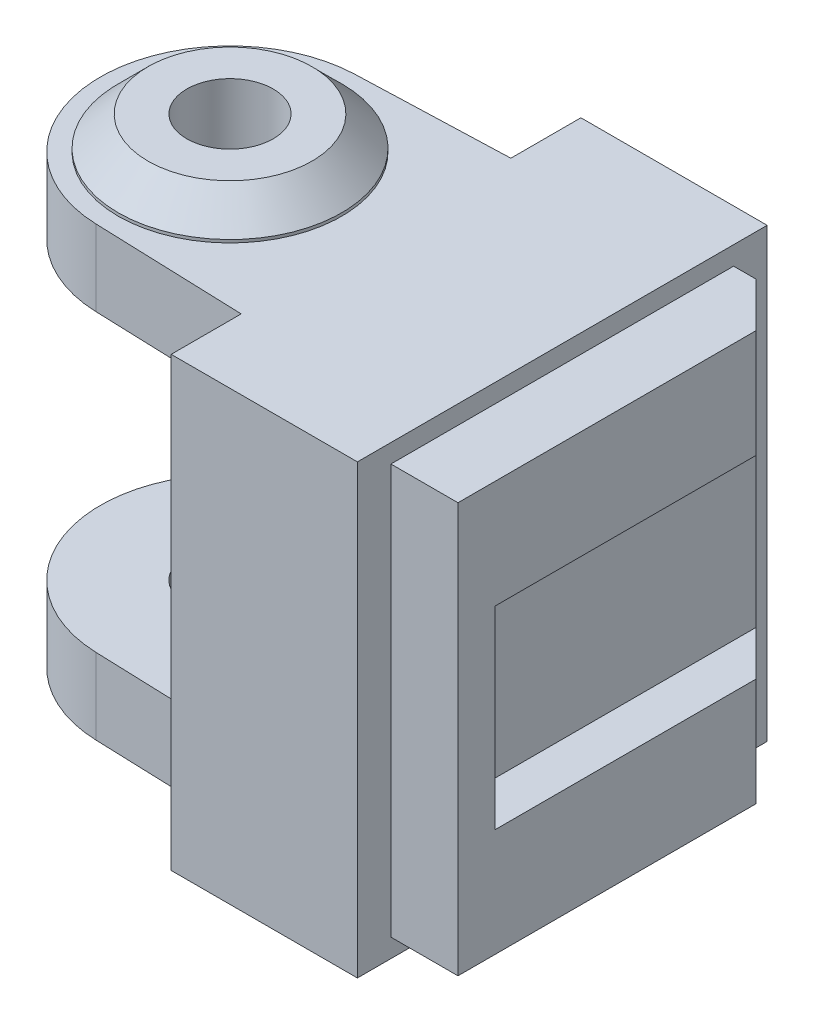
SolidWorks part; units mm, degrees
ref_plane "前视基准面" through (0, 0, 0) normal (0, 0, 1) x (1, 0, 0)
ref_plane "上视基准面" through (0, 0, 0) normal (0, 1, 0) x (1, 0, 0)
ref_plane "右视基准面" through (0, 0, 0) normal (1, 0, 0) x (0, 0, -1)
other "Configuration Table"
sketch "草图1" plane through (0, 0, 0) normal (0, 1, 0) x (1, 0, 0)
  line L0 (-0.3058, 8.6946) -> (9.8, 9.05)
  line L1 (9.8, 9.05) -> (9.8, -9.05)
  line L2 (9.8, -9.05) -> (-0.3058, -8.6946)
  line L3 (0, 0) -> (9.8, 0) construction
  circle A0 centre (0, 0) radius 2.9
  arc A1 (-0.3058, 8.6946) -> (-0.3058, -8.6946) centre (0, 0) ccw
  dimension "D1" = 5.8
  dimension "D4" = 17.4
  dimension "D2" = 9.8
  dimension "D3" = 18.1
extrude "凸台-拉伸1" add sketch "草图1" along normal blind 30
sketch "草图2" plane through (9.8, 0, 0) normal (1, 0, 0) x (0, 0, -1)
  line L0 (0, 30) -> (0, 0) construction
  line L1 (-13.75, 30) -> (13.75, 30)
  line L2 (-13.75, 30) -> (-13.75, 0)
  line L3 (-13.75, 0) -> (13.75, 0)
  line L4 (13.75, 30) -> (13.75, 0)
  line L5 (-9.05, 30) -> (9.05, 30) construction
  line L6 (-9.05, 0) -> (9.05, 0) construction
  dimension "D1" = 27.5
extrude "凸台-拉伸2" add sketch "草图2" along normal blind 17
sketch "草图3" plane through (9.8, 0, 0) normal (-1, 0, 0) x (0, 0, 1)
  line L0 (-13.75, 0) -> (-13.75, 30) construction
  line L1 (-13.75, 24.9) -> (13.75, 24.9)
  line L2 (-13.75, 24.9) -> (-13.75, 5.1)
  line L3 (-13.75, 5.1) -> (13.75, 5.1)
  line L4 (13.75, 24.9) -> (13.75, 5.1)
  line L5 (13.75, 30) -> (13.75, 0) construction
  line L6 (-13.75, 15) -> (13.75, 15) construction
  dimension "D1" = 19.8
extrude "切除-拉伸1" cut sketch "草图3" along normal up to next
sketch "草图4" plane through (26.8, 0, 0) normal (1, 0, 0) x (0, 0, -1)
  line L0 (0, 30) -> (0, 28.75) construction
  line L1 (-11.5, 28.75) -> (11.5, 28.75)
  line L2 (-11.5, 28.75) -> (-11.5, 1.25)
  line L3 (-11.5, 1.25) -> (11.5, 1.25)
  line L4 (-13.75, 30) -> (-13.75, 0)
  line L5 (-13.75, 0) -> (13.75, 0)
  line L6 (13.75, 0) -> (13.75, 30)
  line L7 (13.75, 30) -> (-13.75, 30)
  line L8 (-13.75, 30) -> (-13.75, 0)
  line L9 (-13.75, 0) -> (13.75, 0)
  line L10 (13.75, 0) -> (13.75, 30)
  line L11 (13.75, 30) -> (-13.75, 30)
  line L12 (11.5, 28.75) -> (11.5, 1.25)
  line L13 (-13.75, 15) -> (-11.5, 15) construction
  dimension "D2" = 27.5
  dimension "D3" = 23
  dimension "D1" = 0
extrude "切除-拉伸2" cut sketch "草图4" against normal blind 4.5
chamfer "倒角1" distance 3 angle 45 1 edges at (26.8, 15, -11.5)
sketch "草图5" plane through (26.8, 0, 0) normal (1, 0, 0) x (0, 0, -1)
  line L0 (11.5, 28.75) -> (11.5, 1.25) construction
  line L1 (11.5, 21.5) -> (-9, 21.5)
  line L2 (11.5, 21.5) -> (11.5, 8.5)
  line L3 (11.5, 8.5) -> (-9, 8.5)
  line L4 (-9, 21.5) -> (-9, 8.5)
  line L5 (-11.5, 15) -> (-9, 15) construction
  line L6 (-11.5, 28.75) -> (-11.5, 1.25) construction
  line L7 (-11.5, 28.75) -> (-11.5, 1.25) construction
  dimension "D1" = 13
  dimension "D2" = 2.5
extrude "切除-拉伸3" cut sketch "草图5" against normal blind 3
sketch "草图6" plane through (0, 30, 0) normal (0, 1, 0) x (1, 0, 0)
  circle A0 centre (0, 0) radius 2.9
  circle A1 centre (0, 0) radius 7.5
  circle A2 centre (0, 0) radius 2.9 construction
  dimension "D1" = 15
extrude "凸台-拉伸3" add sketch "草图6" along normal blind 2.2
chamfer "倒角2" distance 2 angle 45 1 edges at (0, 32.2, 7.5)
ref_plane "基准面1" through (0, 15, 0) normal (0, -1, 0) x (-1, 0, 0)
mirror "镜向1" about plane through (0, 15, 0) normal (0, -1, 0) of "凸台-拉伸3", "倒角2"
